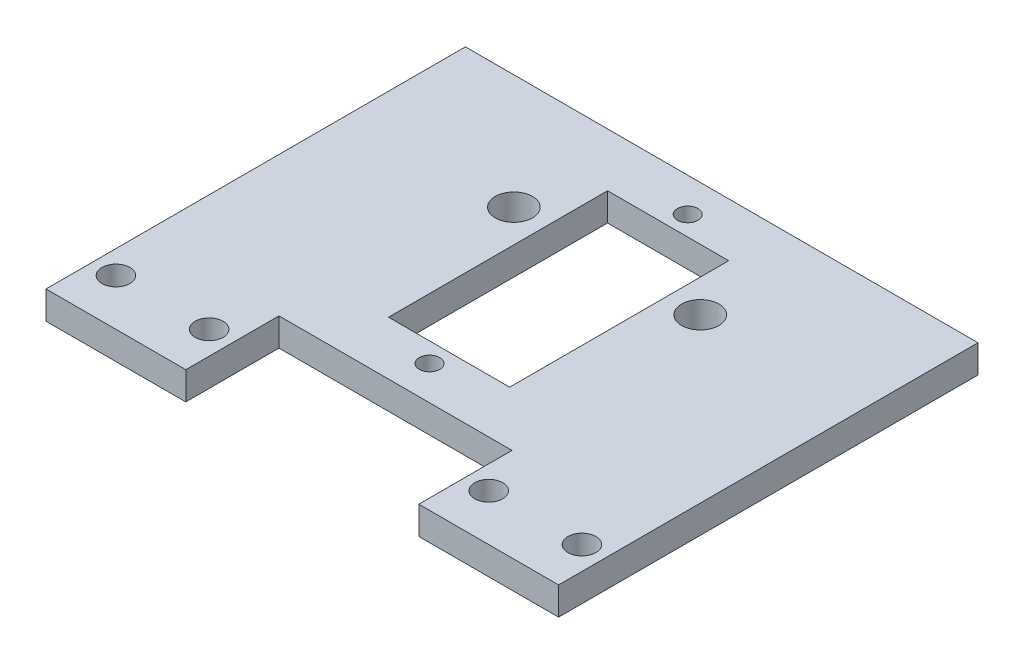
SolidWorks part; units mm, degrees
ref_plane "Front Plane" through (0, 0, 0) normal (0, 0, 1) x (1, 0, 0)
ref_plane "Top Plane" through (0, 0, 0) normal (0, 1, 0) x (1, 0, 0)
ref_plane "Right Plane" through (0, 0, 0) normal (1, 0, 0) x (0, 0, -1)
sketch "Sketch1" plane through (0, 0, 0) normal (0, 1, 0) x (1, 0, 0)
  line L0 (0, 0) -> (15, 0)
  line L1 (15, 0) -> (15, 10)
  line L2 (15, 10) -> (40, 10)
  line L3 (40, 10) -> (40, 0)
  line L4 (40, 0) -> (55, 0)
  line L5 (55, 0) -> (55, 45)
  line L6 (55, 45) -> (0, 45)
  line L7 (0, 45) -> (0, 0)
  line L8 (27.5, 10) -> (27.5, 45) construction
  line L9 (21, 39.25) -> (34, 39.25)
  line L10 (21, 39.25) -> (21, 15.75)
  line L11 (21, 15.75) -> (34, 15.75)
  line L12 (34, 39.25) -> (34, 15.75)
  line L13 (0, 27.5) -> (55, 27.5) construction
  line L14 (27.5, 5) -> (32.5, 5) construction
  line L15 (27.5, 5) -> (22.5, 5) construction
  circle A0 centre (27.5, 5) radius 1.5 construction
  circle A1 centre (32.5, 5) radius 1.5 construction
  circle A2 centre (37.5, 5) radius 1.5 construction
  circle A3 centre (42.5, 5) radius 1.5
  circle A4 centre (47.5, 5) radius 1.5 construction
  circle A5 centre (52.5, 5) radius 1.5
  circle A6 centre (22.5, 5) radius 1.5 construction
  circle A7 centre (17.5, 5) radius 1.5 construction
  circle A8 centre (12.5, 5) radius 1.5
  circle A9 centre (7.5, 5) radius 1.5 construction
  circle A10 centre (2.5, 5) radius 1.5
  circle A11 centre (27.5, 41.35) radius 1.1
  circle A13 centre (27.5, 13.65) radius 1.1
  point P13 (27.5, 39.25)
  point P14 (27.5, 45)
  point P19 (27.5, 27.5)
  point P20 (34, 27.5)
  point P50 (15, 5)
  dimension "D6" = 3
  dimension "D13" = 2.2
  dimension "D14" = 13.85
  dimension "D1" = 23.5
  dimension "D2" = 35
  dimension "D3" = 15
  dimension "D4" = 15
  dimension "D5" = 25
  dimension "D8" = 5
  dimension "D10" = 5
  dimension "D11" = 10
  dimension "D12" = 13
  dimension "D7" = 6
  dimension "D9" = 6
extrude "Boss-Extrude1" add sketch "Sketch1" along normal blind 3
sketch "Sketch2" plane through (0, 3, 0) normal (0, 1, 0) x (1, 0, 0)
  line L0 (27.5, 45) -> (27.5, 10) construction
  line L1 (55, 45) -> (0, 45) construction
  line L2 (15, 10) -> (40, 10) construction
  circle A1 centre (17.5, 32.7) radius 2 construction
  circle A2 centre (17.5, 32.7) radius 2
  circle A3 centre (37.5, 32.7) radius 2
extrude "Cut-Extrude1" cut sketch "Sketch2" against normal through all
